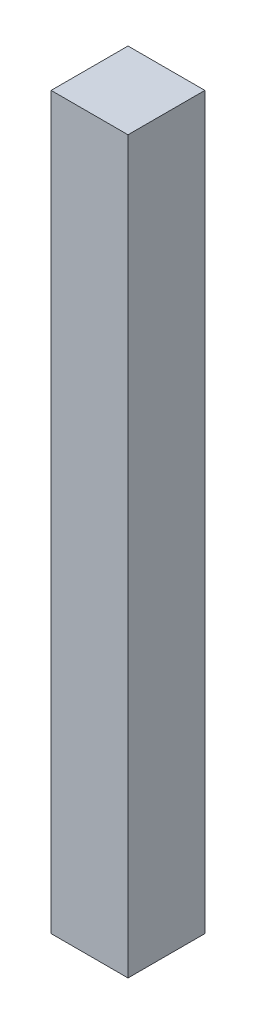
SolidWorks part; units mm, degrees
ref_plane "Спереди" through (0, 0, 0) normal (0, 0, 1) x (1, 0, 0)
ref_plane "Сверху" through (0, 0, 0) normal (0, 1, 0) x (1, 0, 0)
ref_plane "Справа" through (0, 0, 0) normal (1, 0, 0) x (0, 0, -1)
other "Configuration Table"
sketch "Эскиз1" plane through (0, 0, 0) normal (0, 1, 0) x (1, 0, 0)
  line L1 (-10, 10) -> (10, 10)
  line L2 (-10, 10) -> (-10, -10)
  line L3 (-10, -10) -> (10, -10)
  line L4 (10, 10) -> (10, -10)
  line L5 (-10, 10) -> (10, -10) construction
  line L6 (-10, -10) -> (10, 10) construction
  point P0 (0, 0)
  dimension "D1" = 20
extrude "Бобышка-Вытянуть1" add sketch "Эскиз1" along normal mid plane 190
